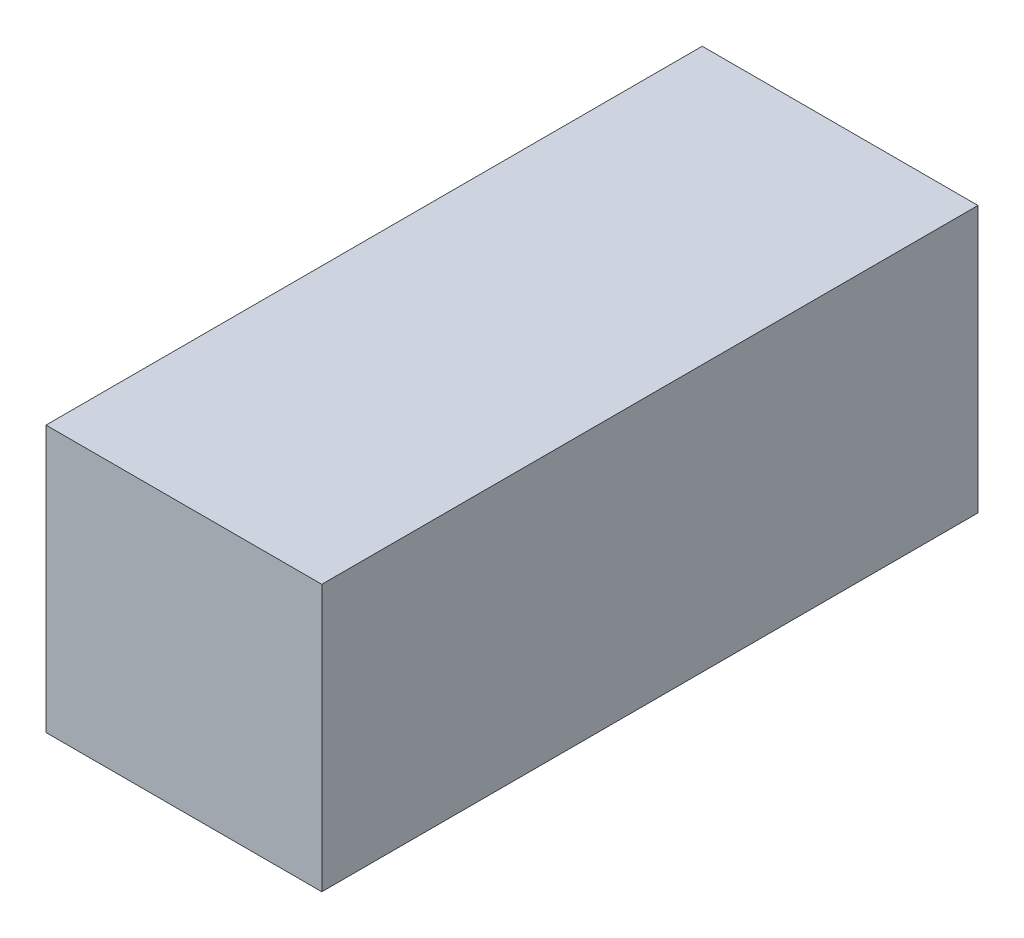
SolidWorks part; units mm, degrees
ref_plane "Front Plane" through (0, 0, 0) normal (0, 0, 1) x (1, 0, 0)
ref_plane "Top Plane" through (0, 0, 0) normal (0, 1, 0) x (1, 0, 0)
ref_plane "Right Plane" through (0, 0, 0) normal (1, 0, 0) x (0, 0, -1)
other "Center of Mass"
sketch "Sketch1" plane through (0, 0, 0) normal (1, 0, 0) x (0, 0, -1)
  line L1 (0, 0) -> (175.26, 0)
  line L2 (0, 0) -> (0, 71.12)
  line L3 (0, 71.12) -> (175.26, 71.12)
  line L4 (175.26, 0) -> (175.26, 71.12)
  dimension "D1" = 71.12
  dimension "D2" = 175.26
extrude "Boss-Extrude1" add sketch "Sketch1" along normal blind 73.66
